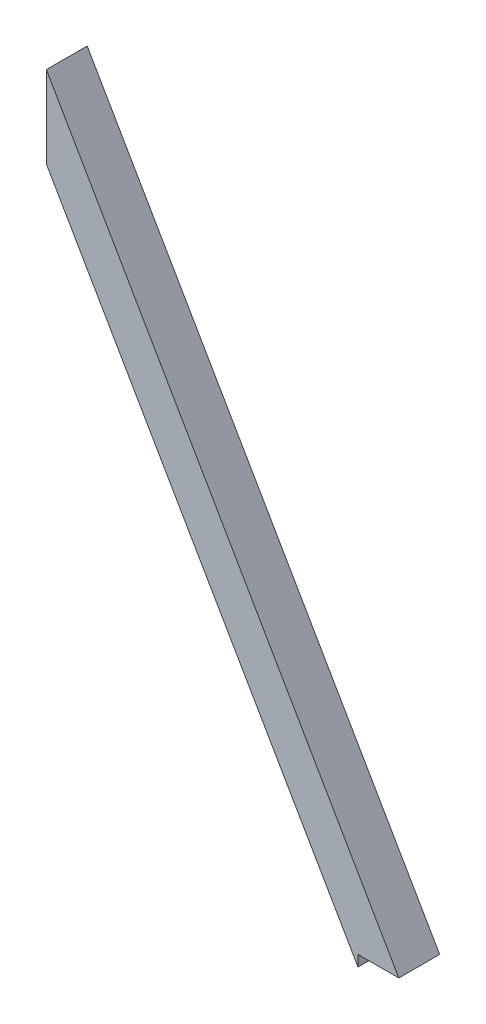
SolidWorks part; units mm, degrees
ref_plane "Front Plane" through (0, 0, 0) normal (0, 0, 1) x (1, 0, 0)
ref_plane "Top Plane" through (0, 0, 0) normal (0, 1, 0) x (1, 0, 0)
ref_plane "Right Plane" through (0, 0, 0) normal (1, 0, 0) x (0, 0, -1)
sketch "Sketch1" plane through (0, 0, 0) normal (0, 0, 1) x (1, 0, 0)
  line L0 (0, 0) -> (219.1893, 0) construction
  line L1 (0, 0) -> (0, 762) construction
  line L2 (193.7893, 0) -> (244.5893, 0) construction
  line L3 (193.7893, 0) -> (193.7893, -25.4) construction
  line L4 (193.7893, -25.4) -> (244.5893, -25.4) construction
  line L5 (244.5893, 0) -> (244.5893, -25.4) construction
  line L6 (193.7893, 0) -> (244.5893, -25.4) construction
  line L7 (193.7893, -25.4) -> (244.5893, 0) construction
  line L8 (219.1893, 0) -> (0, 379.647)
  line L9 (193.7893, -6.8059) -> (0, 328.847)
  line L10 (193.7893, 0) -> (193.7893, -6.8059)
  line L11 (219.1893, 0) -> (193.7893, 0)
  line L12 (0, 328.847) -> (0, 379.647)
  line L13 (197.1923, -12.7) -> (-21.997, 366.947) construction
  point P0 (0, 0)
  point P1 (219.1893, 0)
  point P4 (219.1893, -12.7)
  dimension "D1" = 219.1893
  dimension "D2" = 25.4
  dimension "D3" = 50.8
  dimension "D4" = 762
  dimension "D5" = 60
  dimension "D6" = 25.4
  dimension "D7" = 25.4
  dimension "D8" = 438.3786
extrude "Boss-Extrude1" add sketch "Sketch1" along normal mid plane 25.4
